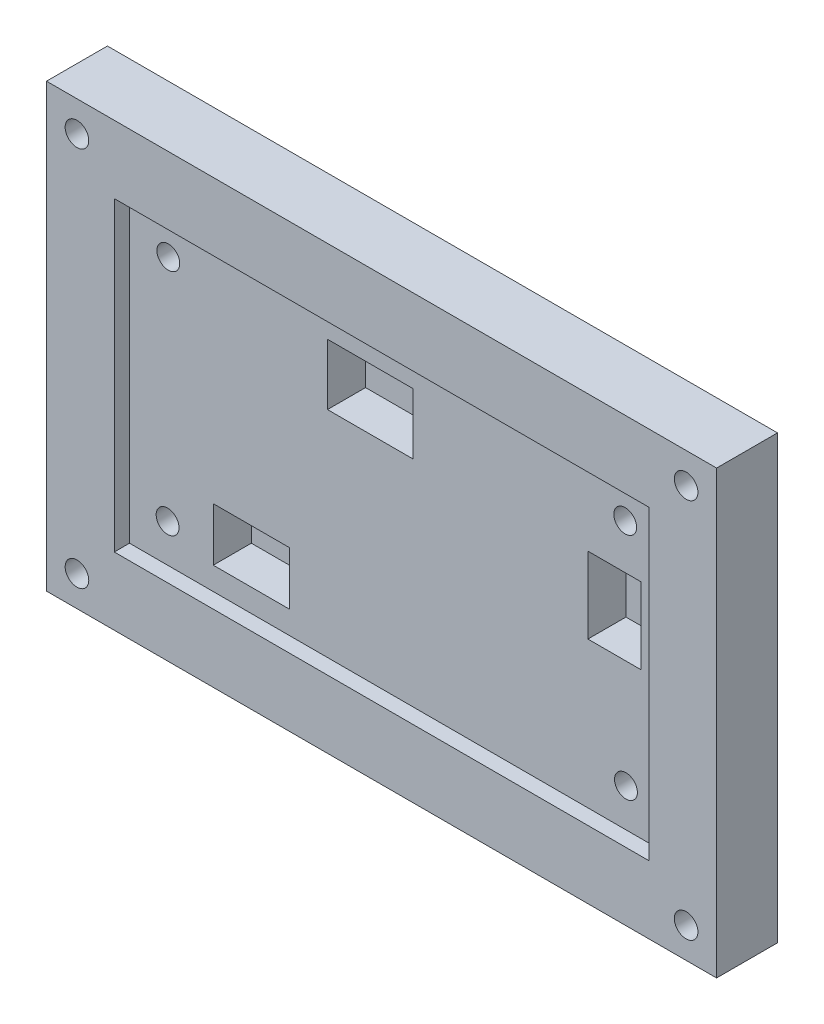
SolidWorks part; units mm, degrees
ref_plane "前视基准面" through (0, 0, 0) normal (0, 0, 1) x (1, 0, 0)
ref_plane "上视基准面" through (0, 0, 0) normal (0, 1, 0) x (1, 0, 0)
ref_plane "右视基准面" through (0, 0, 0) normal (1, 0, 0) x (0, 0, -1)
other "Configuration Table"
sketch "草图2" plane through (0, 0, 0) normal (0, 0, 1) x (1, 0, 0)
  line L0 (0, 29) -> (94.2675, 29) construction
  line L1 (0, 58) -> (88, 58)
  line L2 (0, 58) -> (0, 0)
  line L3 (0, 0) -> (88, 0)
  line L4 (88, 58) -> (88, 0)
  line L5 (44, 58) -> (44, 0) construction
  circle A0 centre (4, 4) radius 1.55
  circle A1 centre (4, 54) radius 1.55
  circle A2 centre (84, 4) radius 1.55
  circle A3 centre (84, 54) radius 1.55
  dimension "D3" = 4
  dimension "D1" = 88
  dimension "D2" = 58
  dimension "D4" = 4
extrude "凸台-拉伸4" add sketch "草图2" along normal blind 8
sketch "草图6" plane through (0, 0, 8) normal (0, 0, 1) x (1, 0, 0)
  line L12 (8.9, 49.1) -> (8.9, 8.9)
  line L13 (8.9, 8.9) -> (79.1, 8.9)
  line L14 (79.1, 8.9) -> (79.1, 49.1)
  line L15 (79.1, 49.1) -> (8.9, 49.1)
  line L16 (8.9, 49.1) -> (8.9, 8.9)
  line L17 (8.9, 8.9) -> (79.1, 8.9)
  line L18 (79.1, 8.9) -> (79.1, 49.1)
  line L19 (79.1, 49.1) -> (8.9, 49.1)
  dimension "D1" = 8.9
extrude "切除-拉伸4" cut sketch "草图6" against normal blind 2
sketch "草图7" plane through (0, 0, 6) normal (0, 0, 1) x (1, 0, 0)
  line L0 (8.9, 8.9) -> (79.1, 8.9) construction
  line L1 (8.9, 49.1) -> (8.9, 8.9) construction
  line L3 (79.1, 49.1) -> (8.9, 49.1) construction
  line L4 (8.9, 49.1) -> (8.9, 8.9) construction
  line L5 (44, 50) -> (44, 8) construction
  line L6 (8.9, 8.9) -> (79.1, 8.9) construction
  line L7 (19.9, 18.9) -> (29.9, 18.9)
  line L8 (19.9, 18.9) -> (19.9, 11.9)
  line L9 (19.9, 11.9) -> (29.9, 11.9)
  line L10 (29.9, 18.9) -> (29.9, 11.9)
  line L11 (69.1, 38.1) -> (76.1, 38.1)
  line L12 (69.1, 38.1) -> (69.1, 28.1)
  line L13 (69.1, 28.1) -> (76.1, 28.1)
  line L14 (76.1, 38.1) -> (76.1, 28.1)
  line L15 (34.9, 45.1) -> (46.1, 45.1)
  line L16 (34.9, 45.1) -> (34.9, 37.1)
  line L17 (34.9, 37.1) -> (46.1, 37.1)
  line L18 (46.1, 45.1) -> (46.1, 37.1)
  line L19 (79.1, 8.9) -> (79.1, 49.1) construction
  line L20 (79.1, 8.9) -> (79.1, 49.1) construction
  line L21 (79.1, 49.1) -> (8.9, 49.1) construction
  circle A0 centre (13.9, 13.9) radius 1.5
  circle A1 centre (14, 44) radius 1.5
  circle A2 centre (74.1, 13.9) radius 1.5
  circle A3 centre (74, 44) radius 1.5
  dimension "D1" = 5
  dimension "D3" = 3
  dimension "D2" = 5
  dimension "D4" = 10
  dimension "D5" = 11
  dimension "D6" = 21
  dimension "D7" = 3
  dimension "D8" = 10
  dimension "D9" = 11
  dimension "D10" = 21
  dimension "D11" = 4
  dimension "D12" = 12
  dimension "D13" = 26
  dimension "D14" = 33
extrude "切除-拉伸7" cut sketch "草图7" against normal blind 5
